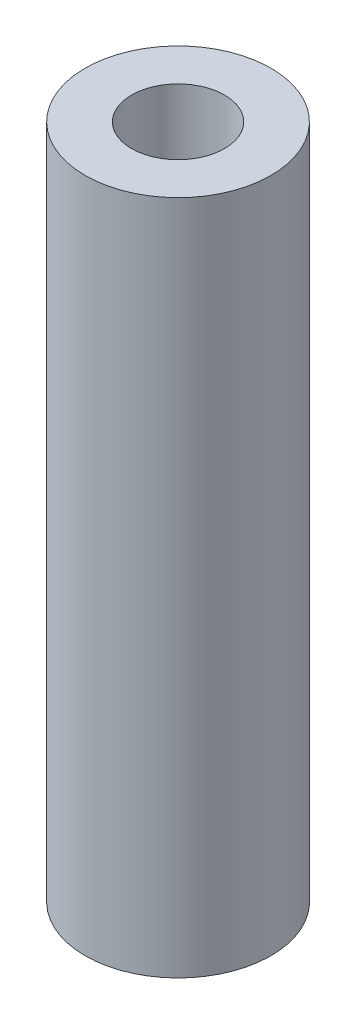
SolidWorks part; units mm, degrees
ref_plane "Front Plane" through (0, 0, 0) normal (0, 0, 1) x (1, 0, 0)
ref_plane "Top Plane" through (0, 0, 0) normal (0, 1, 0) x (1, 0, 0)
ref_plane "Right Plane" through (0, 0, 0) normal (1, 0, 0) x (0, 0, -1)
sketch "Sketch1" plane through (0, 0, 0) normal (0, 1, 0) x (1, 0, 0)
  circle A0 centre (0, 0) radius 11
  dimension "D1" = 22
extrude "Boss-Extrude1" add sketch "Sketch1" along normal blind 80
sketch "Sketch2" plane through (0, 80, 0) normal (0, 1, 0) x (1, 0, 0)
  circle A0 centre (0, 0) radius 5.5
  dimension "D1" = 11
extrude "Cut-Extrude1" cut sketch "Sketch2" against normal up to next
